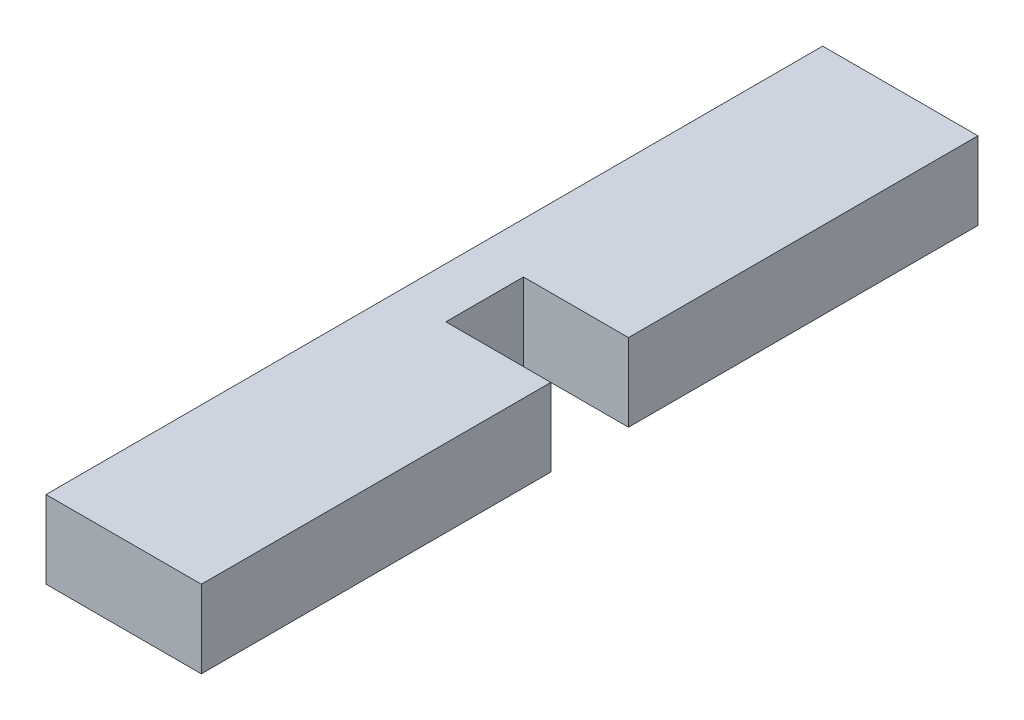
SolidWorks part; units mm, degrees
ref_plane "Front" through (0, 0, 0) normal (0, 0, 1) x (1, 0, 0)
ref_plane "Top" through (0, 0, 0) normal (0, 1, 0) x (1, 0, 0)
ref_plane "Right" through (0, 0, 0) normal (1, 0, 0) x (0, 0, -1)
sketch "Sketch1" plane through (0, 0, 0) normal (0, 1, 0) x (1, 0, 0)
  line L1 (-5, 25) -> (5, 25)
  line L2 (-5, 25) -> (-5, -25)
  line L3 (-5, -25) -> (5, -25)
  line L4 (5, 25) -> (5, -25)
  line L5 (-5, 25) -> (5, -25) construction
  line L6 (-5, -25) -> (5, 25) construction
  point P0 (0, 0)
  dimension "D1" = 50
  dimension "D2" = 10
extrude "Boss-Extrude1" add sketch "Sketch1" along normal blind 5
sketch "Sketch2" plane through (0, 5, 0) normal (0, 1, 0) x (1, 0, 0)
  line L0 (5, 0) -> (5, 2.5)
  line L1 (5, -25) -> (5, 25) construction
  line L3 (5, 2.5) -> (-1.7595, 2.5)
  line L5 (-1.7595, 2.5) -> (-1.7595, -2.5)
  line L6 (-1.7595, -2.5) -> (5, -2.5)
  line L7 (5, -2.5) -> (5, 0)
  dimension "D1" = 2.5
  dimension "D2" = 2.5
extrude "Cut-Extrude1" cut sketch "Sketch2" against normal through all
